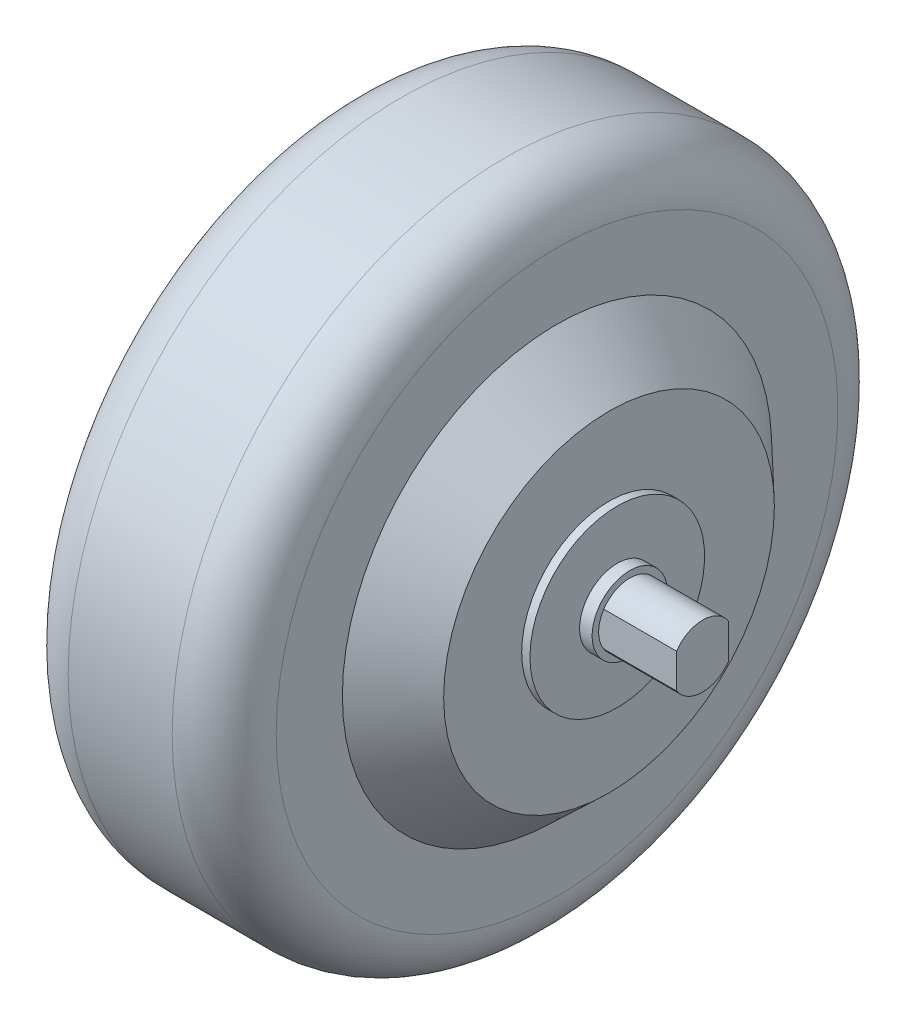
SolidWorks part; units mm, degrees
ref_plane "Front Plane" through (0, 0, 0) normal (0, 0, 1) x (1, 0, 0)
ref_plane "Top Plane" through (0, 0, 0) normal (0, 1, 0) x (1, 0, 0)
ref_plane "Right Plane" through (0, 0, 0) normal (1, 0, 0) x (0, 0, -1)
sketch "Sketch2" plane through (0, 0, 0) normal (0, 0, 1) x (1, 0, 0)
  line L0 (10, 64) -> (-10, 64)
  line L1 (-20, 54) -> (-20, 41.275)
  line L2 (-20, 41.275) -> (-30, 31.795)
  line L3 (-30, 31.795) -> (-30, 16.795)
  line L4 (-30, 16.795) -> (-31.5875, 16.795)
  line L5 (-31.5875, 16.795) -> (-31.5875, 7.25)
  line L6 (-34, 6) -> (-48, 6)
  line L7 (-48, 6) -> (-48, 0)
  line L8 (0, 0) -> (0, 64) construction
  line L9 (48, 6) -> (48, 0)
  line L10 (34, 6) -> (48, 6)
  line L11 (31.5875, 16.795) -> (31.5875, 7.25)
  line L12 (30, 16.795) -> (31.5875, 16.795)
  line L13 (30, 31.795) -> (30, 16.795)
  line L14 (20, 41.275) -> (30, 31.795)
  line L15 (20, 54) -> (20, 41.275)
  line L16 (-48, 0) -> (48, 0)
  line L17 (-34, 6) -> (-34, 7.25)
  line L18 (-34, 7.25) -> (-31.5875, 7.25)
  line L19 (31.5875, 7.25) -> (34, 7.25)
  line L20 (34, 7.25) -> (34, 6)
  arc A0 (10, 64) -> (20, 54) centre (10, 54) cw
  arc A1 (-10, 64) -> (-20, 54) centre (-10, 54) ccw
  point P3 (0, 64)
  point P22 (20, 64)
  point P25 (-20, 64)
  dimension "D9" = 10
  dimension "D1" = 40
  dimension "D2" = 10.795
  dimension "D3" = 6
  dimension "D4" = 64
  dimension "D5" = 60
  dimension "D6" = 1.5875
  dimension "D7" = 15
  dimension "D8" = 41.275
  dimension "D10" = 96
  dimension "D11" = 7.25
  dimension "D12" = 14
revolve "Revolve1" add sketch "Sketch2" angle 360 about L16
sketch "Sketch3" plane through (-48, 0, 0) normal (-1, 0, 0) x (0, 0, 1)
  line L0 (5, 3.3166) -> (5, -3.3166)
  line L2 (-5, 3.3166) -> (-5, -3.3166)
  arc A0 (-5, 3.3166) -> (-5, -3.3166) centre (0, 0) ccw
  circle A1 centre (0, 0) radius 6 construction
  arc A2 (5, -3.3166) -> (5, 3.3166) centre (0, 0) ccw
  dimension "D1" = 10
extrude "Cut-Extrude1" cut sketch "Sketch3" against normal up to surface (82 mm away)
mirror "Mirror1" about plane through (0, 0, 0) normal (1, 0, 0) of "Cut-Extrude1"
